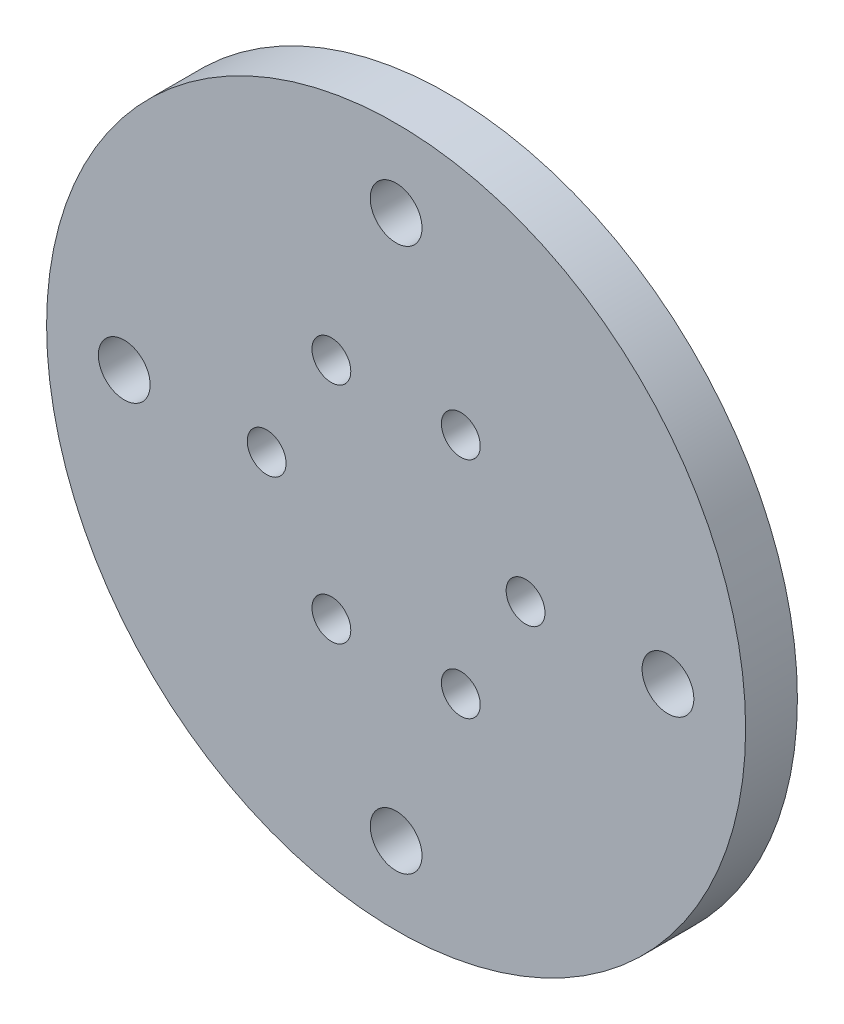
SolidWorks part; units mm, degrees
ref_plane "前视基准面" through (0, 0, 0) normal (0, 0, 1) x (1, 0, 0)
ref_plane "上视基准面" through (0, 0, 0) normal (0, 1, 0) x (1, 0, 0)
ref_plane "右视基准面" through (0, 0, 0) normal (1, 0, 0) x (0, 0, -1)
other "Configuration Table"
sketch "草图1" plane through (0, 0, 0) normal (0, 0, 1) x (1, 0, 0)
  circle A0 centre (0, 0) radius 27
  dimension "D2" = 54
extrude "凸台-拉伸1" add sketch "草图1" along normal blind 4
sketch "草图2" plane through (0, 0, 4) normal (0, 0, 1) x (1, 0, 0)
  line L1 (5, -8.6603) -> (10, 0) construction
  line L2 (10, 0) -> (5, 8.6603) construction
  line L3 (5, 8.6603) -> (-5, 8.6603) construction
  line L4 (-5, 8.6603) -> (-10, 0) construction
  line L5 (-10, 0) -> (-5, -8.6603) construction
  line L6 (-5, -8.6603) -> (5, -8.6603) construction
  circle A0 centre (0, 0) radius 8.6603 construction
  circle A1 centre (5, 8.6603) radius 1.5
  circle A2 centre (10, 0) radius 1.5
  circle A3 centre (5, -8.6603) radius 1.5
  circle A4 centre (-5, -8.6603) radius 1.5
  circle A5 centre (-10, 0) radius 1.5
  circle A6 centre (-5, 8.6603) radius 1.5
  circle A7 centre (0, 21) radius 2
  circle A8 centre (21, 0) radius 2
  circle A9 centre (0, -21) radius 2
  circle A10 centre (-21, 0) radius 2
  dimension "D2" = 3
  dimension "D4" = 4
  dimension "D1" = 10
  dimension "D5" = 21
  dimension "D3" = 6
  dimension "D6" = 4
extrude "切除-拉伸1" cut sketch "草图2" against normal blind 10
chamfer "倒角1" distance 1 angle 45 4 edges at (23, 0, 0) (2, 21, 0) (2, -21, 0) (-19, 0, 0)
